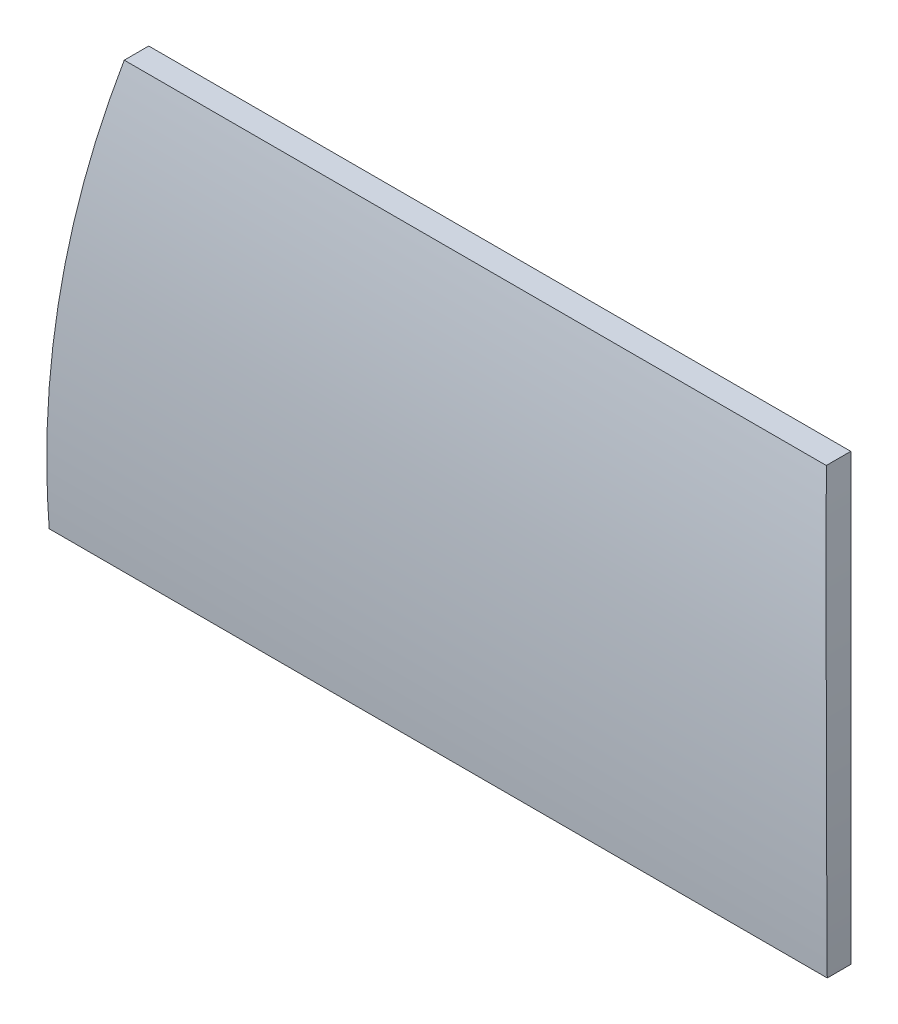
SolidWorks part; units mm, degrees
material "Glass"
ref_plane "Front Plane" through (0, 0, 0) normal (0, 0, 1) x (1, 0, 0)
ref_plane "Top Plane" through (0, 0, 0) normal (0, 1, 0) x (1, 0, 0)
ref_plane "Right Plane" through (0, 0, 0) normal (1, 0, 0) x (0, 0, -1)
sketch "Sketch1" plane through (0, 0, 0) normal (0, 0, 1) x (1, 0, 0)
  line L0 (121.1841, 1295.4) -> (2359.3229, 1295.4)
  line L1 (0, 0) -> (2480.507, 0)
  arc A0 (2359.3229, 1295.4) -> (2480.507, 0) centre (-2557.7141, 182.0449) cw
  arc A1 (121.1841, 1295.4) -> (0, 0) centre (5038.2212, 182.0449) ccw
  dimension "D3" = 5041.509
  dimension "D4" = 5041.509
  dimension "D5" = 182.0449
  dimension "D1" = 2238.1388
  dimension "D2" = 2480.507
extrude "Boss-Extrude1" add sketch "Sketch1" along normal mid plane 508
sketch "Sketch2" plane through (0, 0, 0) normal (1, 0, 0) x (0, 0, -1)
  line L1 (196.1868, 1295.4) -> (254, 1295.4)
  line L3 (254, 1295.4) -> (254, 0)
  line L4 (254, 0) -> (76.2672, 0)
  line L5 (118.0703, 1295.4) -> (-254, 1295.4)
  line L6 (0, 417.7228) -> (0, 0)
  line L7 (0, 0) -> (76.2672, 0)
  line L8 (196.1868, 1295.4) -> (118.0703, 1295.4)
  line L9 (0, 417.7228) -> (0, 0)
  line L10 (-254, 1295.4) -> (-254, 0)
  line L11 (-254, 0) -> (0, 0)
  arc A0 (196.1868, 1295.4) -> (76.2672, 0) centre (5078.4821, 190.1785) ccw
  arc A1 (118.0703, 1295.4) -> (0, 0) centre (4873.7213, 208.8614) ccw
  arc A2 (118.0703, 1295.4) -> (0, 0) centre (4873.7213, 208.8614) ccw
  spline S4 degree 3 poles (118.0703, 1295.4) (94.5648, 1190.445) (74.2845, 1084.7664) (40.4506, 871.8984) (26.8971, 764.7092) (6.8137, 548.7534) (0.2837, 439.9866) (-3.2892, 302.9971) (-3.7742, 275.5476) (-4.1536, 234.2952) (-4.2562, 213.6494) (-4.2275, 192.9741) (-4.1791, 179.184) (-4.1402, 172.2852) (-3.659, 110.214) (-2.2952, 55.0846) (0, 0) knots 0 0 0 0 0.25 0.25 0.5 0.5 0.75 0.75 0.8125 0.8125 0.84375 0.859375 0.859375 0.875 0.875 1 1 1 1
  spline S5 degree 3 poles (76.2672, 0) (75.1005, 27.5617) (73.7059, 68.9228) (72.7021, 117.2098) (72.4057, 137.9111) (72.2378, 151.7136) (72.1687, 158.6169) (71.6812, 220.7208) (72.2017, 275.7138) (76.5602, 440.0755) (83.1946, 548.8269) (103.5954, 764.7556) (117.362, 871.933) (151.7238, 1084.781) (172.319, 1190.4514) (196.1868, 1295.4) knots 0 0 0 0 0.0625 0.09375 0.109375 0.109375 0.125 0.125 0.25 0.25 0.5 0.5 0.75 0.75 1 1 1 1
extrude "Cut-Extrude1" cut sketch "Sketch2" against normal through all and the other way through all contours A1 L5 L10 L11 | L1 A0 L4 L3
ref_plane "Plane1" through (-3.2878, 0, 0) normal (-1, 0, 0) x (0, 0, 1)
ref_plane "Plane2" through (2483.7949, 0, 0) normal (1, 0, 0) x (0, 0, -1)
